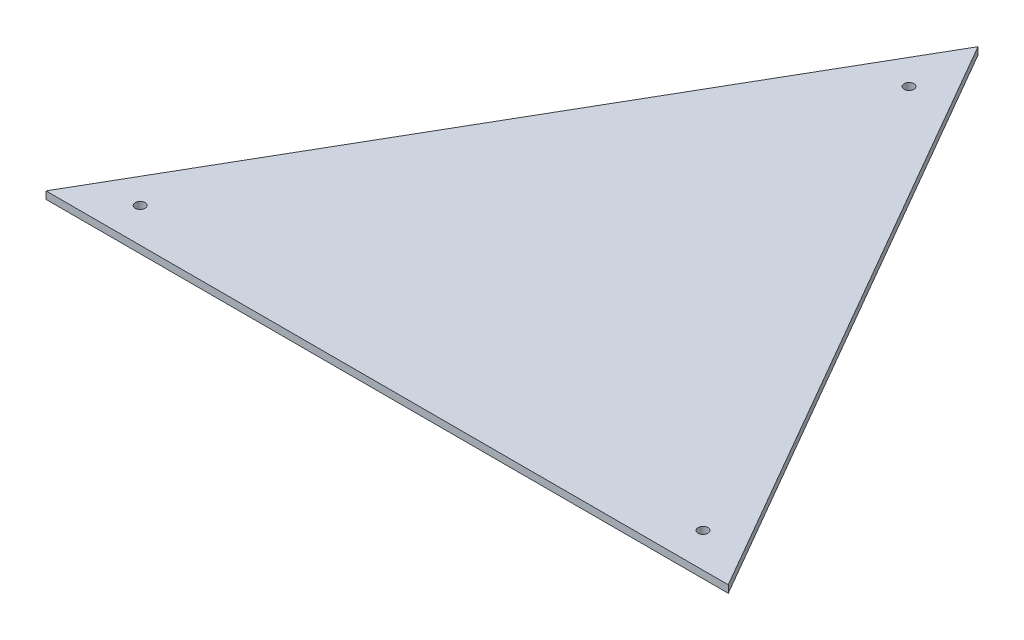
SolidWorks part; units mm, degrees
ref_plane "Front Plane" through (0, 0, 0) normal (0, 0, 1) x (1, 0, 0)
ref_plane "Top Plane" through (0, 0, 0) normal (0, 1, 0) x (1, 0, 0)
ref_plane "Right Plane" through (0, 0, 0) normal (1, 0, 0) x (0, 0, -1)
sketch "Sketch1" plane through (0, 0, 0) normal (0, 1, 0) x (1, 0, 0)
  line L1 (0, 254) -> (-219.9705, -127)
  line L2 (-219.9705, -127) -> (219.9705, -127)
  line L3 (219.9705, -127) -> (0, 254)
  circle A0 centre (0, 0) radius 127 construction
  dimension "D1" = 254
extrude "Boss-Extrude1" add sketch "Sketch1" along normal blind 4.7625
sketch "Sketch2" plane through (0, 4.7625, 0) normal (0, 1, 0) x (1, 0, 0)
  line L0 (0, 254) -> (-219.9705, -127) construction
  line L4 (219.9705, -127) -> (0, 254) construction
  line L5 (-219.9705, -127) -> (219.9705, -127) construction
  circle A0 centre (0, 209.55) radius 3.175
  circle A1 centre (-181.4756, -104.775) radius 3.175
  circle A2 centre (181.4756, -104.775) radius 3.175
  dimension "D2" = 19.05
  dimension "D3" = 6.35
  dimension "D4" = 6.35
  dimension "D6" = 19.05
  dimension "D7" = 19.05
  dimension "D8" = 19.05
  dimension "D9" = 6.35
  dimension "D1" = 19.05
  dimension "D5" = 19.05
extrude "Cut-Extrude1" cut sketch "Sketch2" against normal through all
